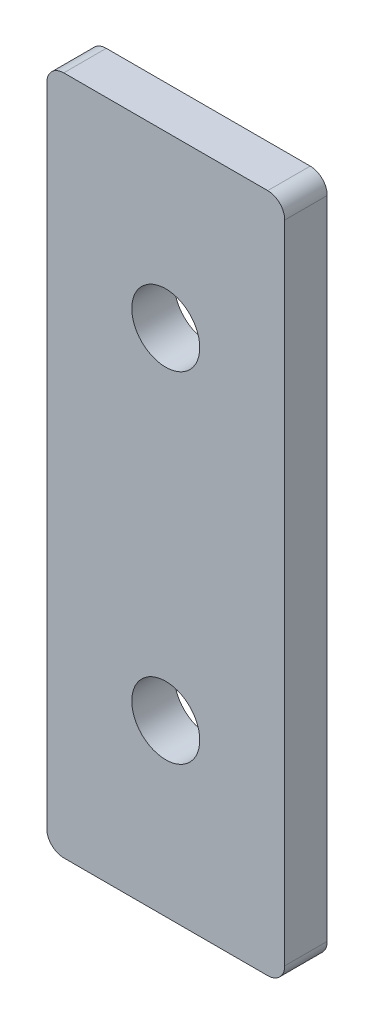
SolidWorks part; units mm, degrees
ref_plane "Front Plane" through (0, 0, 0) normal (0, 0, 1) x (1, 0, 0)
ref_plane "Top Plane" through (0, 0, 0) normal (0, 1, 0) x (1, 0, 0)
ref_plane "Right Plane" through (0, 0, 0) normal (1, 0, 0) x (0, 0, -1)
sketch "Sketch1" plane through (0, 0, 0) normal (0, 0, 1) x (1, 0, 0)
  line L0 (7, 40) -> (7, 0) construction
  line L1 (0, 0) -> (14, 0)
  line L2 (0, 0) -> (0, 40)
  line L3 (0, 40) -> (14, 40)
  line L4 (14, 0) -> (14, 40)
  circle A0 centre (7, 10) radius 2
  circle A1 centre (7, 30) radius 2
  dimension "D2" = 4
  dimension "D1" = 20
  dimension "D3" = 10
  dimension "D4" = 10
  dimension "D5" = 7
  dimension "D6" = 7
extrude "Boss-Extrude1" add sketch "Sketch1" along normal blind 2.5
fillet "Fillet1" radius 1 4 edges at (14, 0, 1.25) (0, 0, 1.25) (0, 40, 1.25) (14, 40, 1.25)
